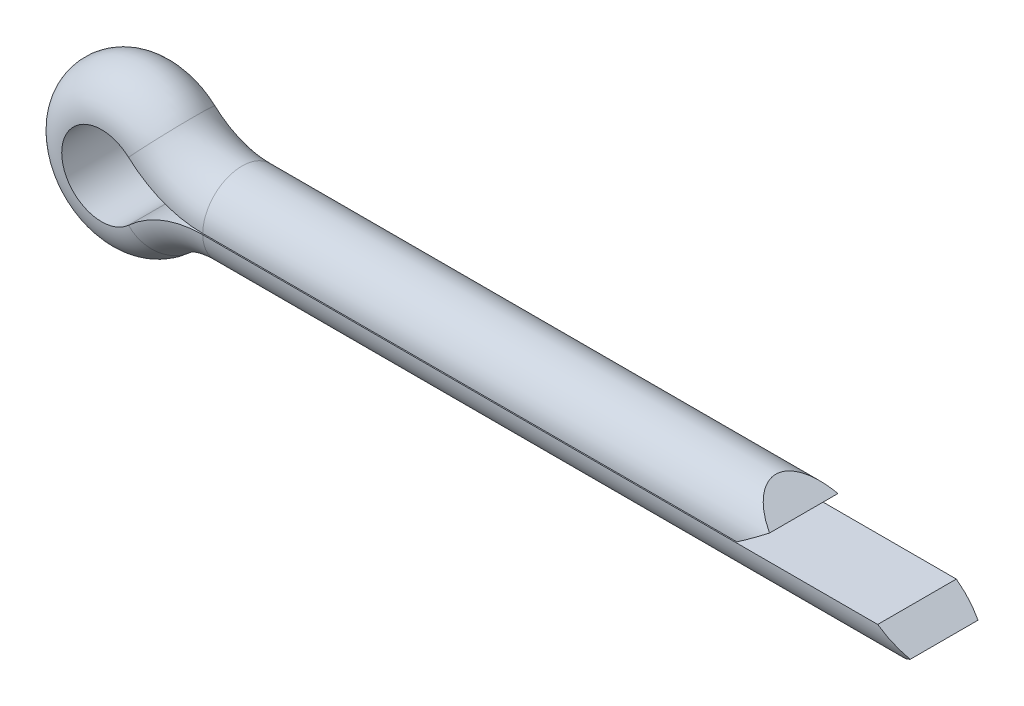
SolidWorks part; units mm, degrees
ref_plane "前视基准面" through (0, 0, 0) normal (0, 0, 1) x (1, 0, 0)
ref_plane "上视基准面" through (0, 0, 0) normal (0, 1, 0) x (1, 0, 0)
ref_plane "右视基准面" through (0, 0, 0) normal (1, 0, 0) x (0, 0, -1)
sketch "尺寸草图" plane through (0, 0, 0) normal (0, 0, 1) x (1, 0, 0)
  line L0 (11.8, 0.7) -> (1.8, 0.7)
  line L1 (1.8, -0.7) -> (14.3, -0.7)
  line L2 (1.8, 0) -> (27.3859, 0) construction
  line L3 (1.8, 0) -> (1.8, -0.0723) construction
  line L4 (-1.4, 0) -> (-1.4, 18.8979) construction
  arc A0 (1.8, 0.7) -> (0.9458, 1.0322) centre (1.8, 1.9643) cw
  arc A1 (0.9458, 1.0322) -> (0.9458, -1.0322) centre (0, 0) ccw
  arc A2 (0.9458, -1.0322) -> (1.8, -0.7) centre (1.8, -1.9643) cw
  dimension "c" = 2.8
  dimension "d1" = 1.4
  dimension "b" = 3.2
  dimension "l" = 10
  dimension "a" = 2.5
ref_plane "基准面1" through (11.8, 0.7, 0) normal (-1, 0, 0) x (0, 0, 1)
sketch "草图2" plane through (11.8, 0.7, 0) normal (-1, 0, 0) x (0, 0, 1)
  line L0 (0, -2.1) -> (0, 0.7) construction
  line L1 (-0.6999, -0.69) -> (0.6999, -0.69)
  arc A0 (0.6999, -0.69) -> (-0.6999, -0.69) centre (0, -0.7) ccw
  dimension "d" = 1.4
  dimension "D1" = 0.01
sweep "扫描2" add profiles "草图2" path "尺寸草图"
sketch "草图3" plane through (0, 0, 0) normal (0, 0, 1) x (1, 0, 0)
  line L0 (1.8, 0) -> (1.8, 16.2682) construction
  line L1 (1.8, 0) -> (37.4999, 0) construction
  line L2 (14.3, -0.7) -> (14.3, -0.01) construction
  line L3 (11.8, 0.345) -> (11.3036, 0.7)
  line L4 (11.8, 0.7) -> (1.8, 0.7) construction
  line L5 (1.8, -0.7) -> (14.3, -0.7) construction
  line L6 (11.8, 0.345) -> (11.2966, 0)
  line L7 (14.3, -0.355) -> (13.8036, 0)
  line L9 (14.3, -0.355) -> (13.7966, -0.7)
  line L10 (13.8036, 0) -> (11.2966, 0)
  line L11 (11.3036, 0.7) -> (14.31, 0.7)
  line L12 (14.31, 0.7) -> (14.31, -0.7)
  line L13 (14.31, -0.7) -> (13.7966, -0.7)
  line L14 (11.8, 0.7) -> (11.8, 0.01) construction
  dimension "D1" = 0.01
  dimension "D3" = 70
  dimension "D4" = 70
extrude "切除-拉伸1" cut sketch "草图3" against normal through all and the other way through all
